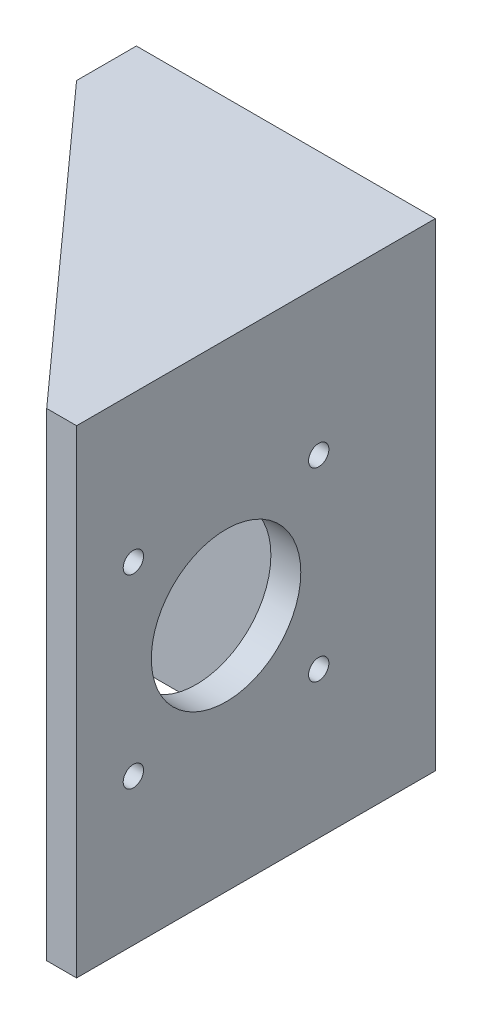
SolidWorks part; units mm, degrees
material "PETG"
ref_plane "Front Plane" through (0, 0, 0) normal (0, 0, 1) x (1, 0, 0)
ref_plane "Top Plane" through (0, 0, 0) normal (0, 1, 0) x (1, 0, 0)
ref_plane "Right Plane" through (0, 0, 0) normal (1, 0, 0) x (0, 0, -1)
sketch "Sketch1" plane through (0, 0, 0) normal (0, 0, 1) x (1, 0, 0)
  line L1 (25, -40) -> (-25, -40)
  line L2 (25, -40) -> (25, 40)
  line L3 (25, 40) -> (-25, 40)
  line L4 (-25, -40) -> (-25, 40)
  line L5 (25, -40) -> (-25, 40) construction
  line L6 (25, 40) -> (-25, -40) construction
  point P0 (0, 0)
  dimension "D1" = 50
  dimension "D2" = 80
extrude "Boss-Extrude1" add sketch "Sketch1" along normal blind 10
sketch "Sketch2" plane through (0, 0, 10) normal (0, 0, 1) x (1, 0, 0)
  line L0 (-25, -40) -> (25, -40) construction
  line L1 (25, 40) -> (20, 40)
  line L2 (25, 40) -> (25, -40)
  line L3 (25, -40) -> (20, -40)
  line L4 (20, 40) -> (20, -40)
  dimension "D1" = 5
extrude "Boss-Extrude2" add sketch "Sketch2" along normal blind 50
sketch "Sketch3" plane through (25, 0, 0) normal (1, 0, 0) x (0, 0, -1)
  line L0 (-60, -40) -> (-60, 40) construction
  line L3 (-60, 0) -> (0, 0) construction
  line L4 (-60, -40) -> (-60, 40) construction
  line L5 (-10, 40) -> (-10, -40) construction
  line L6 (-10, 40) -> (-10, -40) construction
  line L7 (-60, 40) -> (-10, 40) construction
  line L8 (-60, -40) -> (-10, -40) construction
  line L9 (-35, -40) -> (-35, 40) construction
  circle A0 centre (-35, 0) radius 12.5
  dimension "D1" = 25
extrude "Cut-Extrude1" cut sketch "Sketch3" against normal through all
hole_wizard "M3 Clearance Hole1" positions "Sketch4" profile "Sketch5" hole size "M3" standard "ANSI Metric" end condition through all
sketch "Sketch4" plane through (25, 0, 0) normal (1, 0, 0) x (0, 0, -1)
  line L8 (-19.5, -15.5) -> (-50.5, -15.5) construction
  line L9 (-19.5, -15.5) -> (-19.5, 15.5) construction
  line L10 (-19.5, 15.5) -> (-50.5, 15.5) construction
  line L11 (-50.5, -15.5) -> (-50.5, 15.5) construction
  line L12 (-19.5, -15.5) -> (-50.5, 15.5) construction
  line L13 (-19.5, 15.5) -> (-50.5, -15.5) construction
  circle A0 centre (-35, 0) radius 12.5 construction
  circle A1 centre (-35, 0) radius 12.5 construction
  point P17 (-35, 0)
  point P18 (-50.5, 15.5)
  point P187 (-19.5, -15.5)
  point P188 (-19.5, 15.5)
  point P189 (-50.5, -15.5)
  dimension "D1" = 31
  dimension "D2" = 31
sketch "Sketch5" plane through (25, -15.5, 50.5) normal (0, 1, 0) x (0, 0, -1)
  line L0 (0, 0) -> (0, 50)
  line L1 (0, 50) -> (1.7, 50)
  line L2 (1.7, 50) -> (1.7, 0)
  line L5 (1.7, 0) -> (0, 0)
  line L11 (0, -6.35) -> (0, 107.95) construction
  dimension "Thru Hole Dia." = 3.4
  dimension "Thru Hole Depth" = 50
hole_wizard "CBORE for M5 SHCS1" positions "Sketch6" profile "Sketch7" counterbore size "M5" standard "ANSI Metric" end condition through all
sketch "Sketch6" plane through (0, 0, 10) normal (0, 0, 1) x (1, 0, 0)
  line L0 (-2.5, 40) -> (-2.5, -40) construction
  line L1 (20, 40) -> (-25, 40) construction
  line L2 (-25, -40) -> (20, -40) construction
  line L4 (-25, 0) -> (20, 0) construction
  line L5 (-25, 40) -> (-25, -40) construction
  line L6 (20, 40) -> (20, -40) construction
  point P0 (-15.9029, 24.76)
  point P2 (10.9029, 24.76)
  point P4 (-15.9029, -24.76)
  point P28 (10.9029, -24.76)
  point P33 (-15.9029, 24.76)
  dimension "D1" = 15.24
  dimension "D2" = 15.24
sketch "Sketch7" plane through (-15.9029, 24.76, 10) normal (1, 0, 0) x (0, -1, 0)
  line L0 (0, 0) -> (0, 10)
  line L1 (0, 10) -> (2.75, 10)
  line L3 (2.75, 10) -> (2.75, 5)
  line L4 (2.75, 5) -> (5, 5)
  line L5 (5, 5) -> (5, 0)
  line L7 (5, 0) -> (0, 0)
  line L11 (0, -6.35) -> (0, 107.95) construction
  dimension "Thru Hole Dia." = 5.5
  dimension "Thru Hole Depth" = 10
  dimension "C'Bore Dia." = 10
  dimension "C'Bore Depth" = 5
fillet "Fillet11" radius 2 1 edges at (20, 0, 10)
sketch "Sketch8" plane through (0, 40, 0) normal (0, 1, 0) x (1, 0, 0)
  line L0 (-25, -10) -> (20, -60)
  line L1 (20, -60) -> (20, -10)
  line L2 (-25, -10) -> (20, -10)
extrude "Boss-Extrude3" add sketch "Sketch8" against normal blind 6.35
